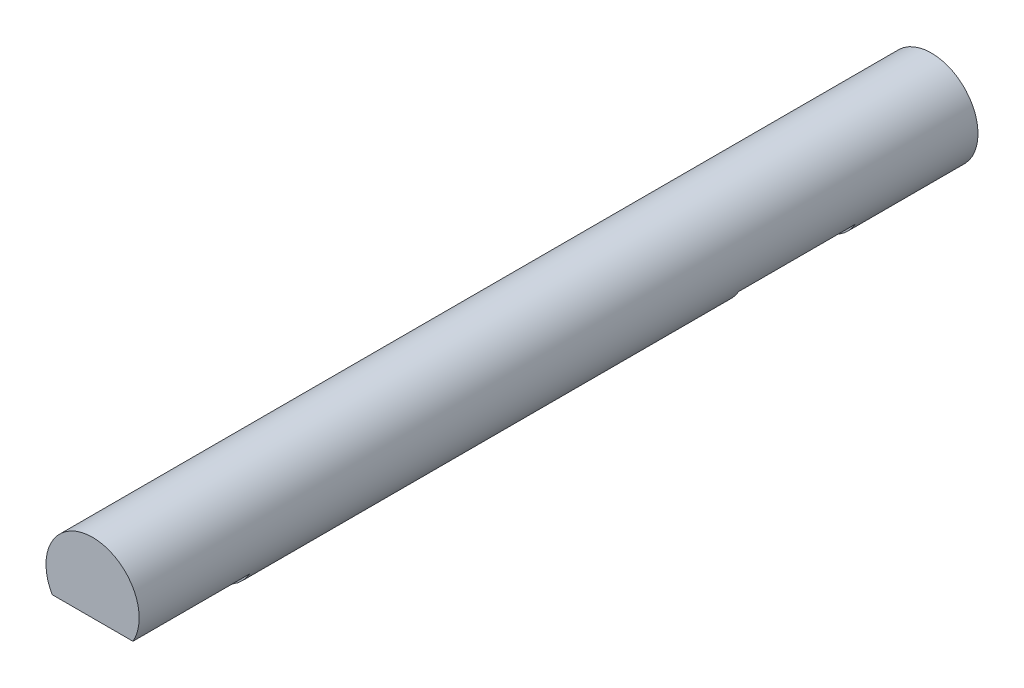
SolidWorks part; units mm, degrees
ref_plane "Front Plane" through (0, 0, 0) normal (0, 0, 1) x (1, 0, 0)
ref_plane "Top Plane" through (0, 0, 0) normal (0, 1, 0) x (1, 0, 0)
ref_plane "Right Plane" through (0, 0, 0) normal (1, 0, 0) x (0, 0, -1)
sketch "Sketch1" plane through (0, 0, 0) normal (0, 0, 1) x (1, 0, 0)
  circle A0 centre (0, 0) radius 2
  dimension "D1" = 4
extrude "Boss-Extrude1" add sketch "Sketch1" along normal blind 36
sketch "Sketch2" plane through (0, 0, 36) normal (0, 0, 1) x (1, 0, 0)
  line L0 (-1.7321, -1) -> (1.7321, -1)
  circle A0 centre (0, 0) radius 2 construction
  circle A2 centre (0, 0) radius 2
  arc A3 (-1.7321, -1) -> (1.7321, -1) centre (0, 0) ccw
  point P4 (0, -1)
  dimension "D1" = 1
  dimension "D2" = 0
extrude "Cut-Extrude1" cut sketch "Sketch2" against normal blind 5
ref_plane "Plane1" through (0, 0, 5) normal (0, 0, -1) x (-1, 0, 0)
sketch "Sketch3" plane through (0, 0, 5) normal (0, 0, -1) x (-1, 0, 0)
  line L1 (1.7321, -1) -> (-1.7321, -1)
  line L2 (1.7321, -1) -> (-1.7321, -1)
  arc A1 (-1.7321, -1) -> (1.7321, -1) centre (0, 0) ccw
  arc A2 (-1.7321, -1) -> (1.7321, -1) centre (0, 0) ccw
  dimension "D1" = 0
extrude "Cut-Extrude2" cut sketch "Sketch3" against normal blind 5
